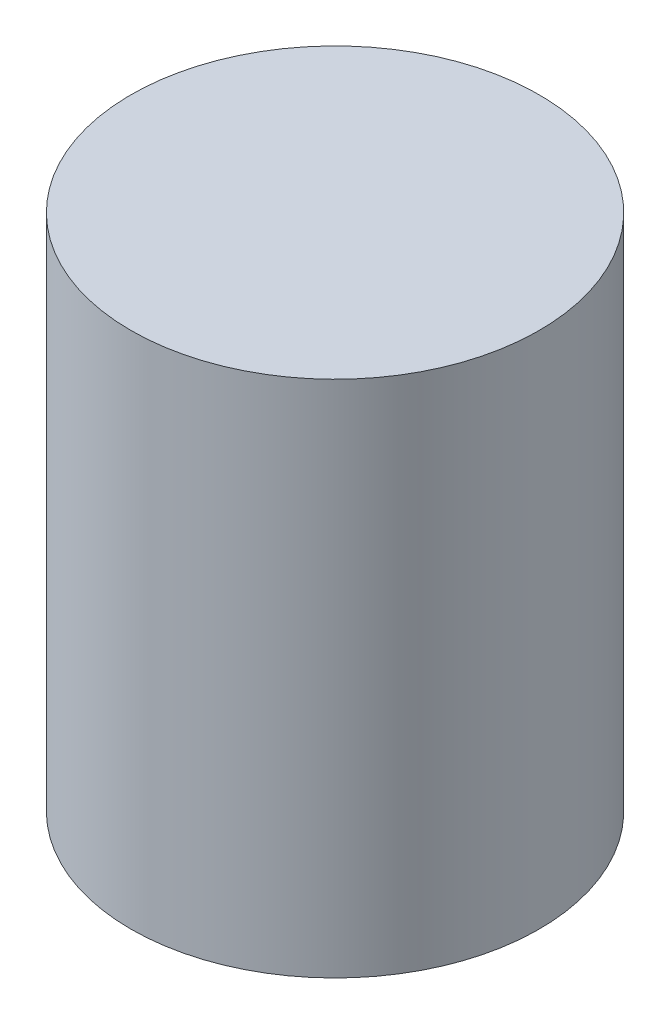
SolidWorks part; units mm, degrees
material "1023 Carbon Steel Sheet (SS)"
ref_plane "Front Plane" through (0, 0, 0) normal (0, 0, 1) x (1, 0, 0)
ref_plane "Top Plane" through (0, 0, 0) normal (0, 1, 0) x (1, 0, 0)
ref_plane "Right Plane" through (0, 0, 0) normal (1, 0, 0) x (0, 0, -1)
sketch "Sketch1" plane through (0, 0, 0) normal (0, 1, 0) x (1, 0, 0)
  circle A0 centre (0, 0) radius 25
  dimension "D1" = 50
extrude "Boss-Extrude1" add sketch "Sketch1" along normal blind 63.5
